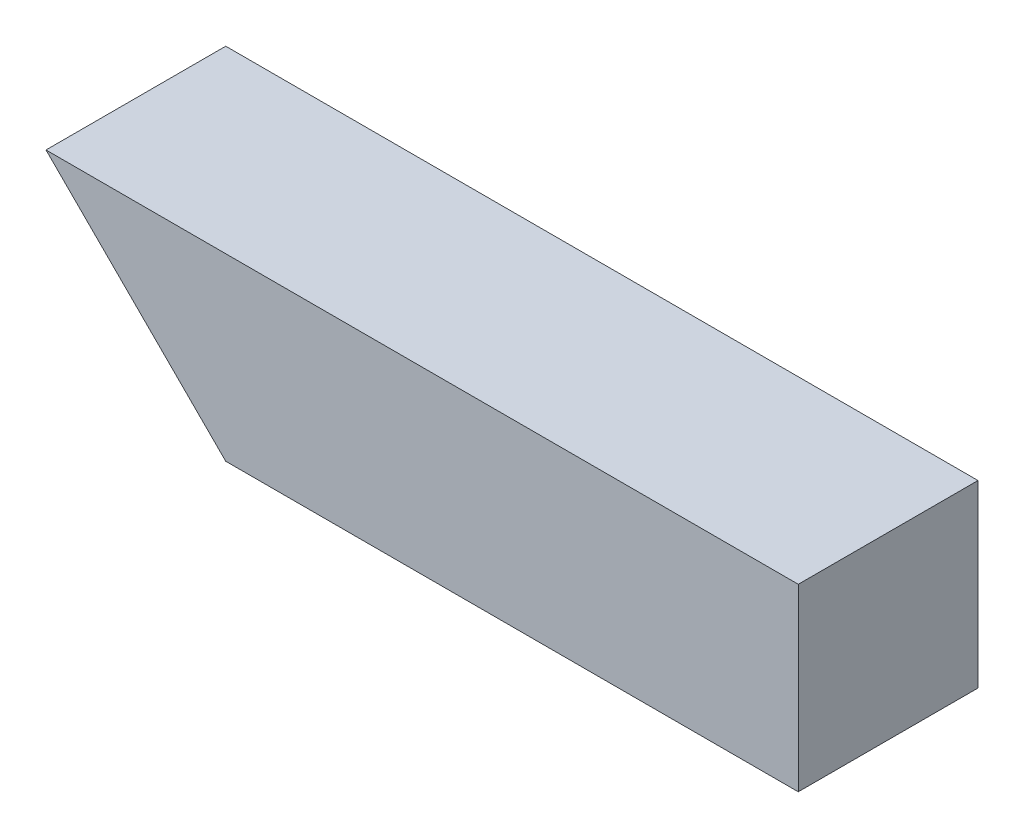
SolidWorks part; units mm, degrees
ref_plane "Front Plane" through (0, 0, 0) normal (0, 0, 1) x (1, 0, 0)
ref_plane "Top Plane" through (0, 0, 0) normal (0, 1, 0) x (1, 0, 0)
ref_plane "Right Plane" through (0, 0, 0) normal (1, 0, 0) x (0, 0, -1)
sketch "Sketch1" plane through (0, 0, 0) normal (1, 0, 0) x (0, 0, -1)
  line L1 (0, 0) -> (38.1, 0)
  line L2 (0, 0) -> (0, -38.1)
  line L3 (0, -38.1) -> (38.1, -38.1)
  line L4 (38.1, 0) -> (38.1, -38.1)
  dimension "D1" = 38.1
  dimension "D2" = 38.1
extrude "Boss-Extrude1" add sketch "Sketch1" along normal blind 159.4649
sketch "Sketch2" plane through (0, 0, 0) normal (0, 0, 1) x (1, 0, 0)
  line L0 (0, -38.1) -> (38.1, -38.1)
  line L1 (159.4649, -38.1) -> (0, -38.1) construction
  line L2 (38.1, -38.1) -> (0, 0)
  dimension "D1" = 38.1
extrude "Cut-Extrude1" cut sketch "Sketch2" against normal through all and the other way through all contours L0 L2
